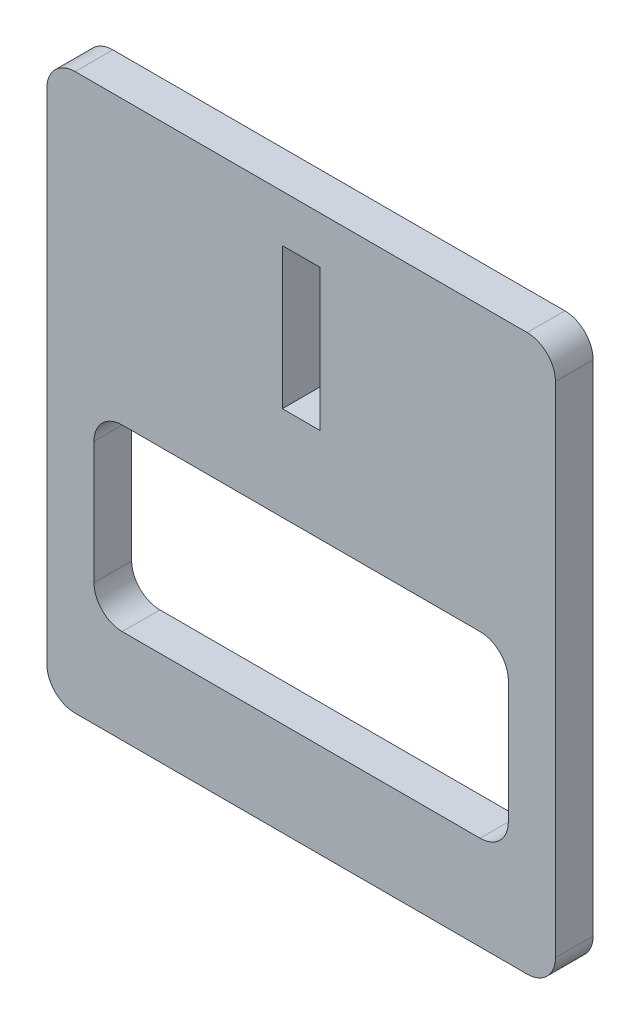
SolidWorks part; units mm, degrees
ref_plane "Front Plane" through (0, 0, 0) normal (0, 0, 1) x (1, 0, 0)
ref_plane "Top Plane" through (0, 0, 0) normal (0, 1, 0) x (1, 0, 0)
ref_plane "Right Plane" through (0, 0, 0) normal (1, 0, 0) x (0, 0, -1)
sketch "Sketch1" plane through (0, 0, 0) normal (0, 0, 1) x (1, 0, 0)
  line L0 (22, 49) -> (22, 16.9517) construction
  line L1 (3, 0) -> (41, 0)
  line L2 (0, 3) -> (0, 16)
  line L3 (3, 19) -> (41, 19)
  line L4 (44, 3) -> (44, 16)
  line L5 (-2, -10) -> (46, -10)
  line L6 (-5, -7) -> (-5, 46)
  line L7 (-2, 49) -> (46, 49)
  line L8 (49, -7) -> (49, 46)
  line L10 (20, 29) -> (24, 29)
  line L11 (20, 29) -> (20, 44)
  line L12 (20, 44) -> (24, 44)
  line L13 (24, 29) -> (24, 44)
  line L14 (20, 29) -> (24, 44) construction
  line L15 (20, 44) -> (24, 29) construction
  arc A0 (41, 19) -> (44, 16) centre (41, 16) cw
  arc A1 (41, 0) -> (44, 3) centre (41, 3) ccw
  arc A2 (3, 0) -> (0, 3) centre (3, 3) cw
  arc A3 (0, 16) -> (3, 19) centre (3, 16) cw
  arc A4 (-5, 46) -> (-2, 49) centre (-2, 46) cw
  arc A5 (46, 49) -> (49, 46) centre (46, 46) cw
  arc A6 (46, -10) -> (49, -7) centre (46, -7) ccw
  arc A7 (-2, -10) -> (-5, -7) centre (-2, -7) cw
  point P7 (44, 19)
  point P10 (44, 0)
  point P13 (0, 0)
  point P16 (0, 19)
  point P23 (22, 36.5)
  dimension "D3" = 3
  dimension "D11" = 3
  dimension "D1" = 44
  dimension "D2" = 19
  dimension "D4" = 10
  dimension "D5" = 5
  dimension "D6" = 5
  dimension "D7" = 30
  dimension "D8" = 10
  dimension "D9" = 15
  dimension "D10" = 4
extrude "Boss-Extrude1" add sketch "Sketch1" along normal blind 4
